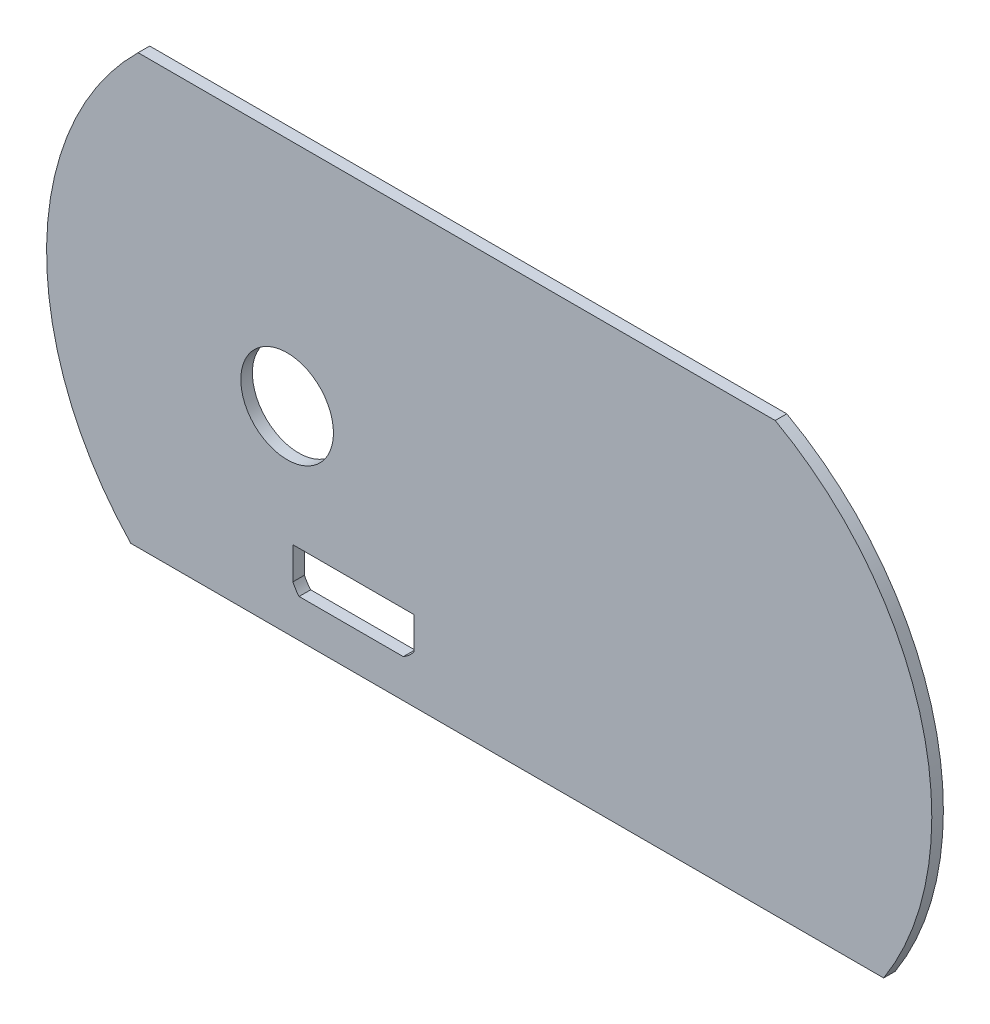
SolidWorks part; units mm, degrees
ref_plane "前视基准面" through (0, 0, 0) normal (0, 0, 1) x (1, 0, 0)
ref_plane "上视基准面" through (0, 0, 0) normal (0, 1, 0) x (1, 0, 0)
ref_plane "右视基准面" through (0, 0, 0) normal (1, 0, 0) x (0, 0, -1)
sketch "草图1" plane through (0, 0, 0) normal (0, 0, 1) x (1, 0, 0)
  line L31 (-30.3089, 18.5) -> (24.6911, 18.5)
  line L32 (34.0559, -18.5) -> (-30.9441, -18.5)
  line L33 (-16.9441, -11.6039) -> (-6.4848, -11.6039)
  line L34 (-16.9441, -11.6039) -> (-16.9441, -14.3836)
  line L35 (-6.4848, -11.6039) -> (-6.4848, -14.3836)
  line L36 (-16.4118, -15.2081) -> (-7.4127, -15.2081)
  arc A23 (-30.3089, 18.5) -> (-30.9441, -18.5) centre (-11.8487, -0.3224) ccw
  arc A24 (24.6911, 18.5) -> (34.0559, -18.5) centre (12.1136, -4.3685) cw
  circle A25 centre (-17.4441, -1.5) radius 4
  arc A26 (-16.9441, -14.3836) -> (-16.4118, -15.2081) centre (-14.112, -13.1394) ccw
  arc A27 (-6.4848, -14.3836) -> (-7.4127, -15.2081) centre (-8.9149, -12.5832) cw
  point P6 (-26.8628, -18.5)
  point P11 (-17.4441, -5.5)
  point P12 (-21.4441, -1.5)
  dimension "D1" = 65
  dimension "D2" = 55
  dimension "D6" = 14
  dimension "D5" = 17
  dimension "D3" = 8
  dimension "D4" = 13.5
extrude "凸台-拉伸1" add sketch "草图1" along normal blind 1
